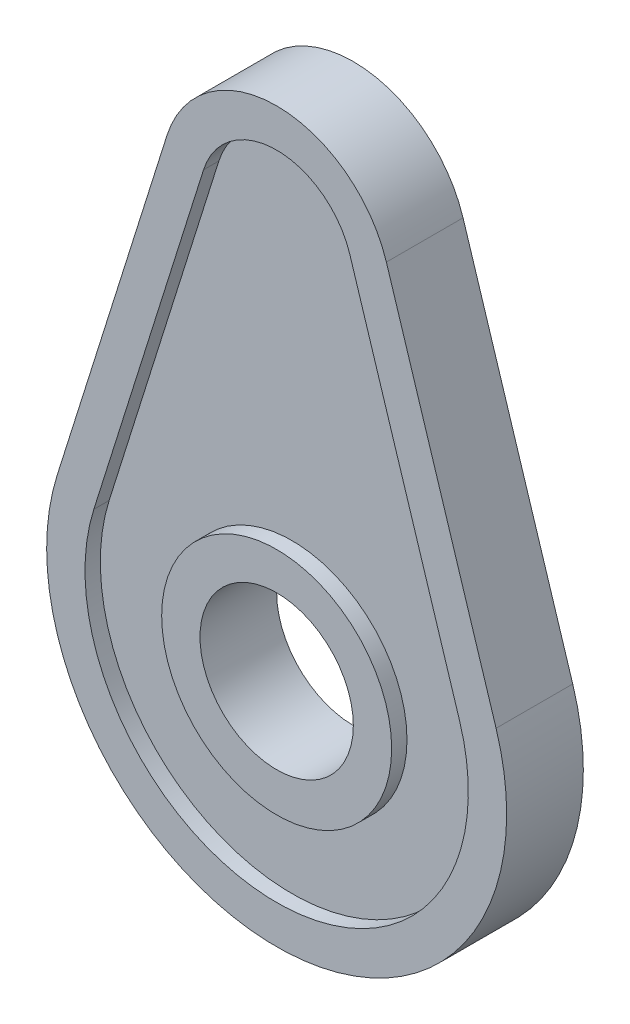
SolidWorks part; units mm, degrees
ref_plane "Front Plane" through (0, 0, 0) normal (0, 0, 1) x (1, 0, 0)
ref_plane "Top Plane" through (0, 0, 0) normal (0, 1, 0) x (1, 0, 0)
ref_plane "Right Plane" through (0, 0, 0) normal (1, 0, 0) x (0, 0, -1)
sketch "Sketch2" plane through (0, 0, 0) normal (0, 0, 1) x (1, 0, 0)
  line L0 (0, 50) -> (0, 0) construction
  line L1 (-14.3091, 54.5) -> (-28.6182, 9)
  line L2 (14.3091, 54.5) -> (28.6182, 9)
  arc A0 (-28.6182, 9) -> (28.6182, 9) centre (0, 0) ccw
  arc A1 (14.3091, 54.5) -> (-14.3091, 54.5) centre (0, 50) ccw
  dimension "D1" = 30
  dimension "D2" = 60
  dimension "D3" = 50
extrude "Boss-Extrude1" add sketch "Sketch2" along normal blind 10
sketch "Sketch3" plane through (0, 0, 10) normal (0, 0, 1) x (1, 0, 0)
  line L4 (-9.5394, 53) -> (-23.8485, 7.5)
  line L5 (23.8485, 7.5) -> (9.5394, 53)
  line L6 (-9.5394, 53) -> (-23.8485, 7.5)
  line L7 (23.8485, 7.5) -> (9.5394, 53)
  arc A4 (9.5394, 53) -> (-9.5394, 53) centre (0, 50) ccw
  arc A5 (-23.8485, 7.5) -> (23.8485, 7.5) centre (0, 0) ccw
  arc A6 (9.5394, 53) -> (-9.5394, 53) centre (0, 50) ccw
  arc A7 (-23.8485, 7.5) -> (23.8485, 7.5) centre (0, 0) ccw
  dimension "D1" = 5
extrude "Cut-Extrude1" cut sketch "Sketch3" against normal blind 2
sketch "Sketch5" plane through (0, 0, 0) normal (0, 0, -1) x (-1, 0, 0)
  line L4 (-9.5394, 53) -> (-23.8485, 7.5)
  line L5 (23.8485, 7.5) -> (9.5394, 53)
  line L6 (-9.5394, 53) -> (-23.8485, 7.5)
  line L7 (23.8485, 7.5) -> (9.5394, 53)
  arc A4 (9.5394, 53) -> (-9.5394, 53) centre (0, 50) ccw
  arc A5 (-23.8485, 7.5) -> (23.8485, 7.5) centre (0, 0) ccw
  arc A6 (9.5394, 53) -> (-9.5394, 53) centre (0, 50) ccw
  arc A7 (-23.8485, 7.5) -> (23.8485, 7.5) centre (0, 0) ccw
  dimension "D1" = 5
extrude "Cut-Extrude3" cut sketch "Sketch5" against normal blind 2
sketch "Sketch6" plane through (0, 0, 8) normal (0, 0, 1) x (1, 0, 0)
  circle A0 centre (0, -0.109) radius 15
  dimension "D1" = 30
extrude "Boss-Extrude2" add sketch "Sketch6" along normal blind 2
sketch "Sketch7" plane through (0, 0, 10) normal (0, 0, 1) x (1, 0, 0)
  circle A0 centre (0, 0) radius 10
  dimension "D1" = 20
extrude "Cut-Extrude4" cut sketch "Sketch7" against normal through all
sketch "Sketch8" plane through (0, 0, 2) normal (0, 0, -1) x (-1, 0, 0)
  circle A0 centre (0, 0) radius 15
  circle A1 centre (0, 0) radius 10 construction
  circle A2 centre (0, 0) radius 10
  dimension "D1" = 30
extrude "Boss-Extrude3" add sketch "Sketch8" along normal blind 2
